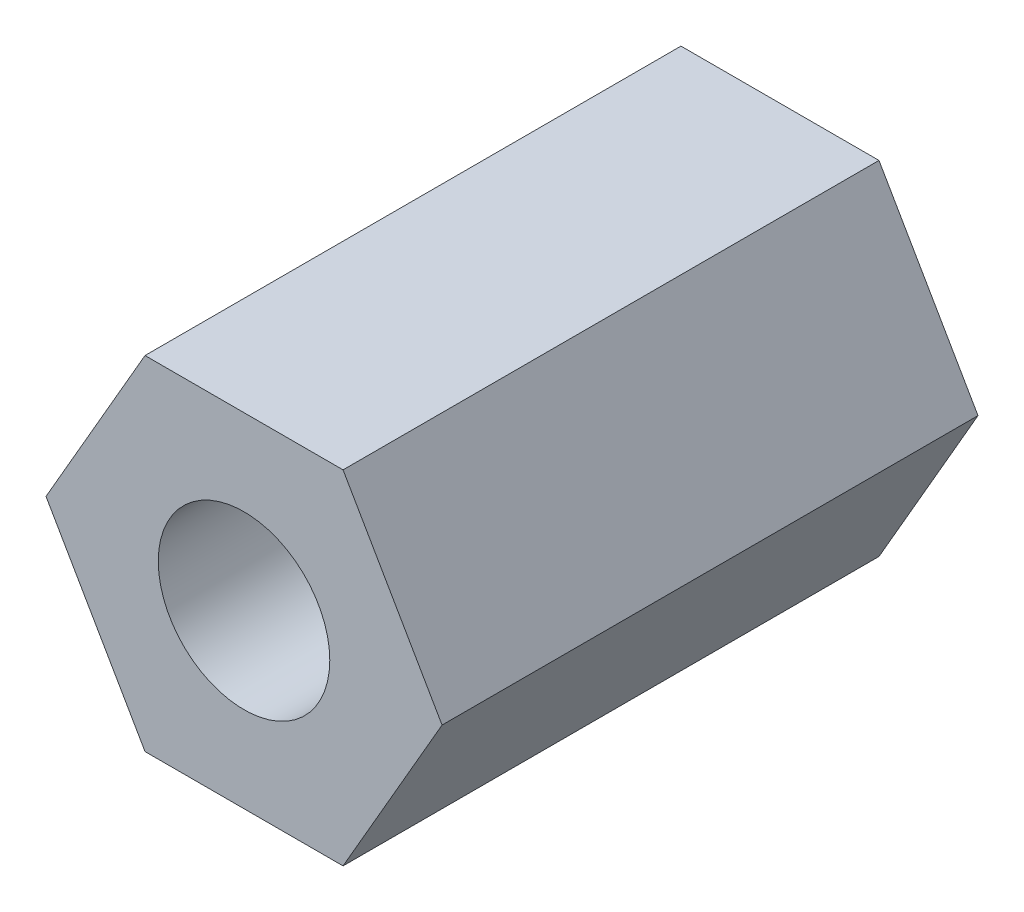
SolidWorks part; units mm, degrees
ref_plane "前视基准面" through (0, 0, 0) normal (0, 0, 1) x (1, 0, 0)
ref_plane "上视基准面" through (0, 0, 0) normal (0, 1, 0) x (1, 0, 0)
ref_plane "右视基准面" through (0, 0, 0) normal (1, 0, 0) x (0, 0, -1)
sketch "草图1" plane through (0, 0, 0) normal (0, 0, 1) x (1, 0, 0)
  line L0 (-28.6627, 0) -> (33.6774, 0) construction
  line L1 (0.9238, -1.6) -> (1.8475, 0)
  line L2 (1.8475, 0) -> (0.9238, 1.6)
  line L3 (0.9238, 1.6) -> (-0.9238, 1.6)
  line L4 (-0.9238, 1.6) -> (-1.8475, 0)
  line L5 (-1.8475, 0) -> (-0.9238, -1.6)
  line L6 (-0.9238, -1.6) -> (0.9238, -1.6)
  circle A0 centre (0, 0) radius 1.6 construction
  dimension "D1" = 3.2
extrude "拉伸1" add sketch "草图1" along normal blind 5
sketch "草图2" plane through (0, 0, 5) normal (0, 0, 1) x (1, 0, 0)
  circle A0 centre (0, 0) radius 1
  dimension "D1" = 2
hole_wizard "M2 螺纹孔1" positions "3D草图2" profile "草图5" tap size "M2" standard "Iso"
sketch3d "3D草图2"
  point P0 (0, 0, 0)
  point P2 (0, 0, 0)
  point P3 (0, 0, 0)
  point P4 (0, 0, 0)
cosmetic thread "孔螺蚊线1" parameters "D1"=4, "D2"=2
sketch "草图5" plane through (0, 0, 0) normal (1, 0, 0) x (0, 1, 0)
  line L0 (0, 0) -> (0, 6.4807)
  line L1 (0, 6.4807) -> (0.8, 6)
  line L2 (0.8, 6) -> (0.8, 0)
  line L5 (0.8, 0) -> (0, 0)
  line L10 (0, 6.4807) -> (-0.8, 6) construction
  line L11 (0, -6.35) -> (0, 107.95) construction
  dimension "蹟恇謂郰芛眻噤" = 1.6
  dimension "蹟恇謂郰芛旮僅" = 6
  dimension "絳芛褒僅" = 118
cosmetic thread "孔螺蚊线2" parameters "D1"=4, "D2"=2
cosmetic thread "孔螺蚊线3" parameters "D1"=4, "D2"=2
cosmetic thread "孔螺蚊线4" parameters "D1"=4, "D2"=2
sketch "草图6" plane through (0, 0, 0) normal (0, 0, -1) x (-1, 0, 0)
  circle A0 centre (0, 0) radius 1.5
  dimension "D1" = 3
extrude "拉伸3" [suppressed] add sketch "草图6" along normal blind 10
